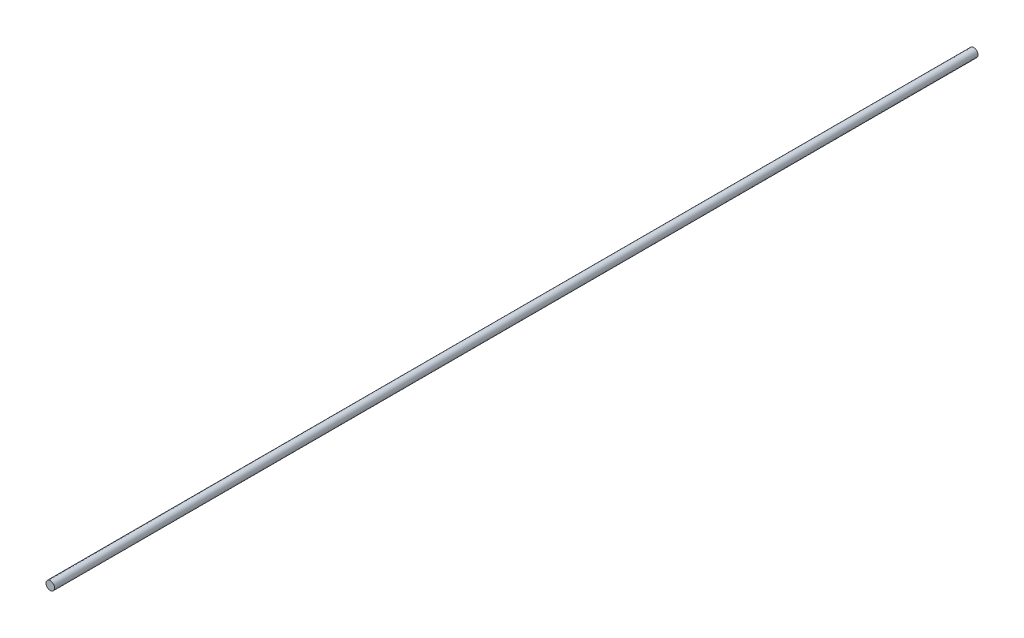
SolidWorks part; units mm, degrees
ref_plane "Front Plane" through (0, 0, 0) normal (0, 0, 1) x (1, 0, 0)
ref_plane "Top Plane" through (0, 0, 0) normal (0, 1, 0) x (1, 0, 0)
ref_plane "Right Plane" through (0, 0, 0) normal (1, 0, 0) x (0, 0, -1)
sketch "Sketch1" plane through (0, 0, 0) normal (0, 0, 1) x (1, 0, 0)
  circle A0 centre (0, 0) radius 3.175
  dimension "D1" = 6.35
extrude "Boss-Extrude1" add sketch "Sketch1" along normal blind 685.8
